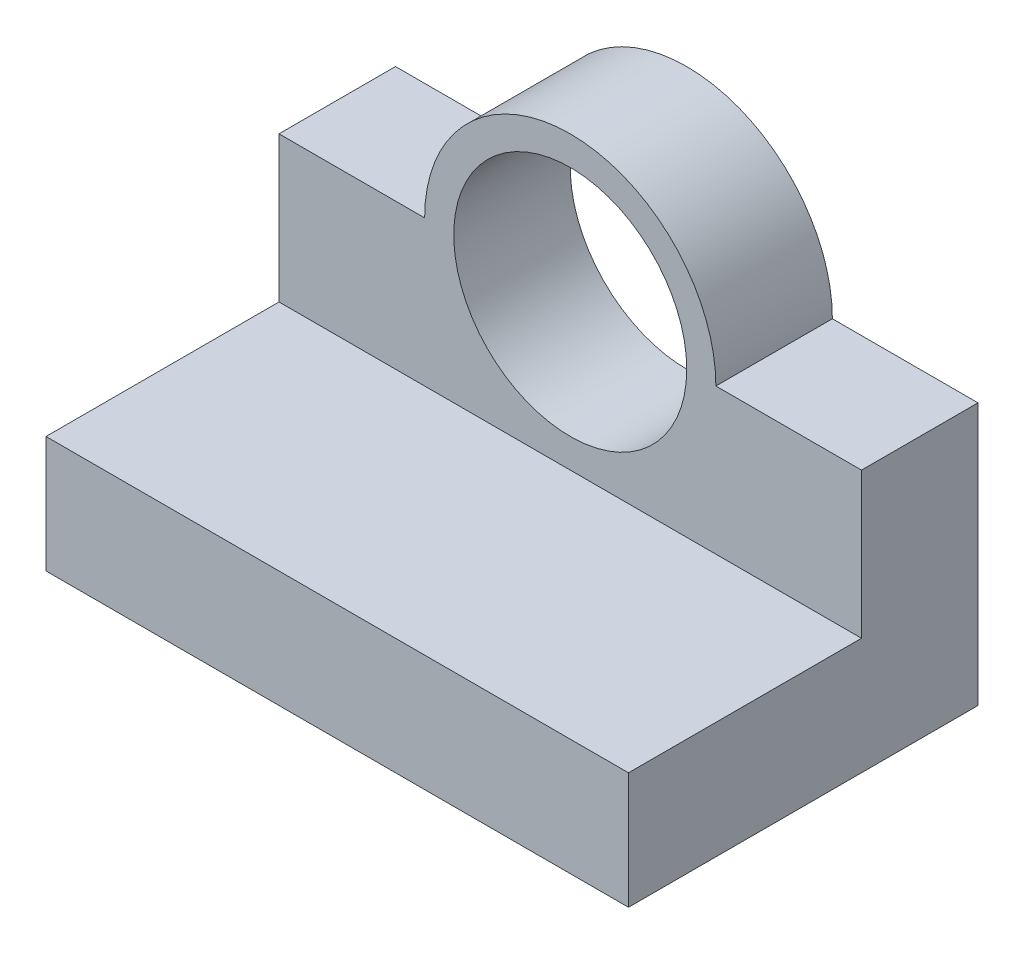
SolidWorks part; units mm, degrees
ref_plane "Ön Düzlem" through (0, 0, 0) normal (0, 0, 1) x (1, 0, 0)
ref_plane "Üst Düzlem" through (0, 0, 0) normal (0, 1, 0) x (1, 0, 0)
ref_plane "Sağ Düzlem" through (0, 0, 0) normal (1, 0, 0) x (0, 0, -1)
sketch "Çizim2" plane through (0, 0, 0) normal (0, 0, 1) x (1, 0, 0)
  line L0 (-35.617, -12.6489) -> (64.383, -12.6489)
  line L1 (-35.617, 12.3511) -> (-10.617, 12.3511)
  line L2 (-35.617, 12.3511) -> (-35.617, -32.6489)
  line L3 (-35.617, -32.6489) -> (64.383, -32.6489)
  line L4 (64.383, 12.3511) -> (64.383, -32.6489)
  line L5 (39.383, 12.3511) -> (64.383, 12.3511)
  circle A0 centre (14.383, 12.3511) radius 20
  arc A1 (-10.617, 12.3511) -> (39.383, 12.3511) centre (14.383, 12.3511) cw
  dimension "D4" = 40
  dimension "D5" = 25
  dimension "D1" = 45
  dimension "D2" = 100
  dimension "D3" = 20
  dimension "D6" = 50
extrude "Yükseklik-Ekstrüzyon2" add sketch "Çizim2" along normal blind 20 contours A1 L1 L2 L0 L4 L5 A0 | L4 L0 L2 L3
sketch "Çizim3" plane through (0, 0, 20) normal (0, 0, 1) x (1, 0, 0)
  line L0 (-35.617, -12.6489) -> (64.383, -12.6489)
  line L1 (-35.617, 12.3511) -> (-35.617, -32.6489) construction
  line L2 (64.383, 12.3511) -> (64.383, -32.6489) construction
  dimension "D1" = 20
extrude "Ekstrüzyon-İnce1" add sketch "Çizim3" along normal blind 40 thin
